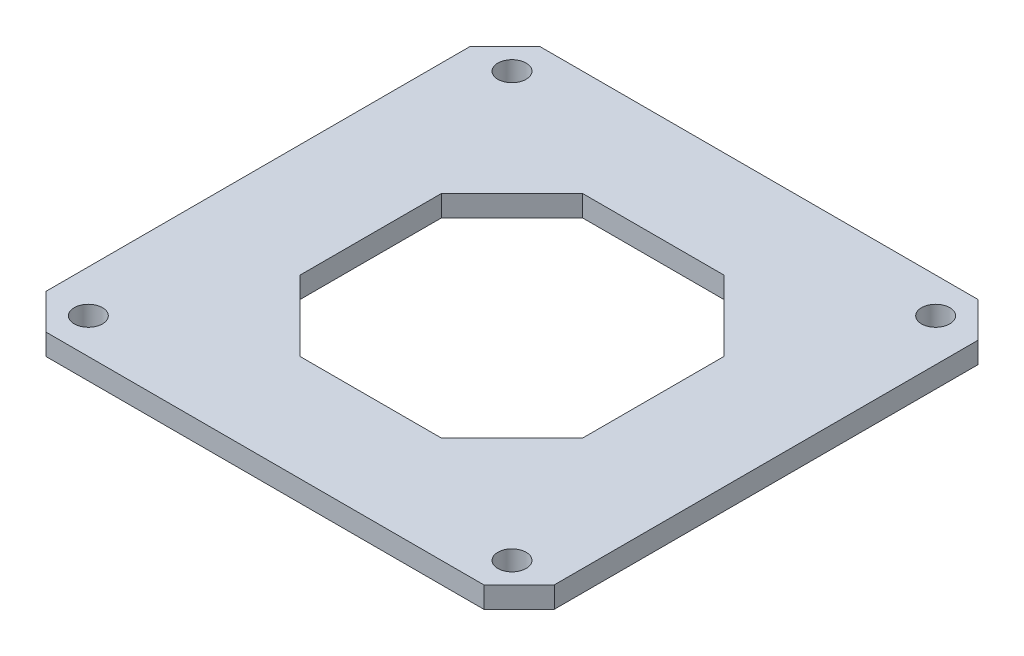
SolidWorks part; units mm, degrees
material "Thornel Mat VMA"
ref_plane "前视基准面" through (0, 0, 0) normal (0, 0, 1) x (1, 0, 0)
ref_plane "上视基准面" through (0, 0, 0) normal (0, 1, 0) x (1, 0, 0)
ref_plane "右视基准面" through (0, 0, 0) normal (1, 0, 0) x (0, 0, -1)
other "Configuration Table"
sketch "草图1" plane through (0, 0, 0) normal (0, 1, 0) x (1, 0, 0)
  line L0 (0, 0) -> (59.8431, 0) construction
  line L1 (-36, -35) -> (36, -35)
  line L2 (-36, -35) -> (-36, 35)
  line L3 (-36, 35) -> (36, 35)
  line L4 (36, -35) -> (36, 35)
  line L5 (-36, -35) -> (36, 35) construction
  line L6 (-36, 35) -> (36, -35) construction
  line L7 (0, 0) -> (0, 58.6165) construction
  line L9 (-20, -20) -> (20, -20)
  line L10 (-20, -20) -> (-20, 20)
  line L11 (0, 0) -> (92.0496, 0) construction
  line L12 (-20, 20) -> (20, 20)
  line L13 (20, -20) -> (20, 20)
  line L14 (-20, -20) -> (20, 20) construction
  line L15 (-20, 20) -> (20, -20) construction
  line L19 (0, 0) -> (68.8105, 0) construction
  line L20 (0, 0) -> (0, -55.2167) construction
  line L21 (0, -5) -> (40.6816, -5) construction
  circle A8 centre (-30, 30) radius 2
  circle A9 centre (30, 30) radius 2
  circle A10 centre (30, -30) radius 2
  circle A11 centre (-30, -30) radius 2
  point P0 (0, 0)
  dimension "D4" = 4
  dimension "D5" = 60
  dimension "D8" = 60
  dimension "D10" = 5
  dimension "D1" = 72
  dimension "D2" = 70
  dimension "D6" = 0
  dimension "D11" = 0
  dimension "D13" = 40
  dimension "40" = 40
extrude "凸台-拉伸1" add sketch "草图1" along normal blind 3
chamfer "倒角1" distance 10 angle 45 4 edges at (-20, 1.5, 20) (20, 1.5, 20) (20, 1.5, -20) (-20, 1.5, -20)
chamfer "倒角2" distance 5 angle 45 4 edges at (36, 1.5, -35) (36, 1.5, 35) (-36, 1.5, 35) (-36, 1.5, -35)
